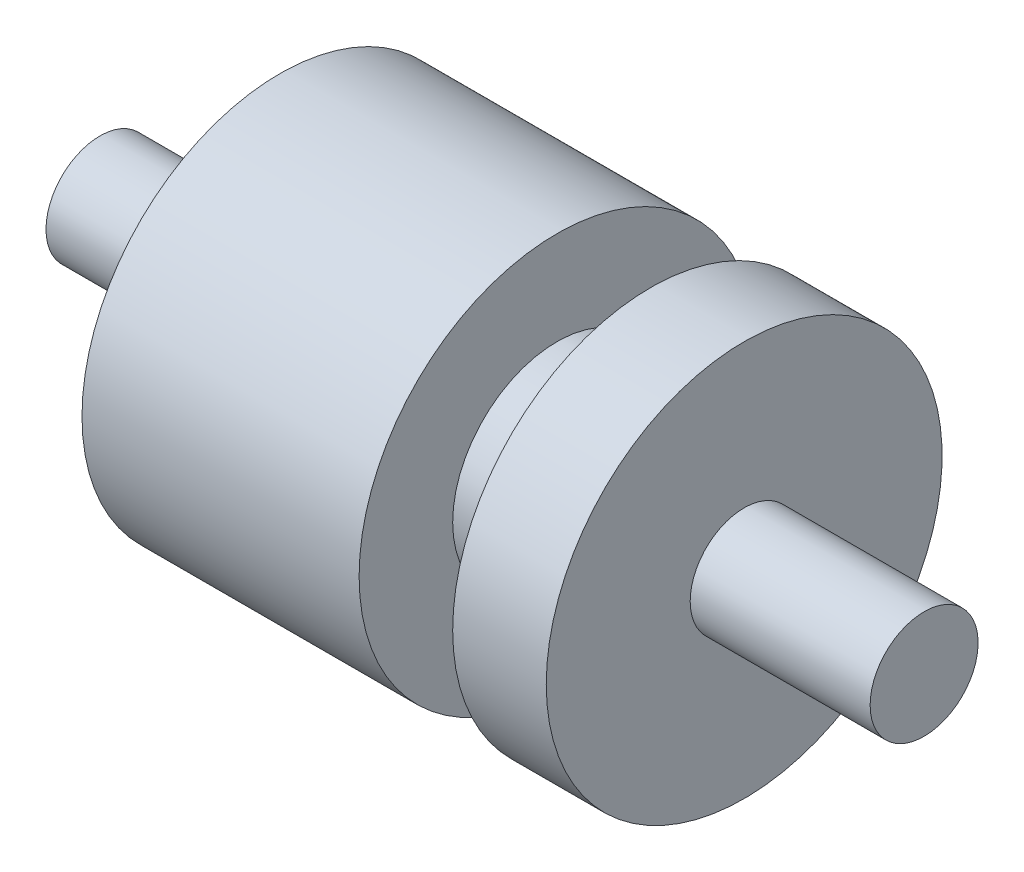
SolidWorks part; units mm, degrees
ref_plane "Alzado" through (0, 0, 0) normal (0, 0, 1) x (1, 0, 0)
ref_plane "Planta" through (0, 0, 0) normal (0, 1, 0) x (1, 0, 0)
ref_plane "Vista lateral" through (0, 0, 0) normal (1, 0, 0) x (0, 0, -1)
sketch "Croquis2" plane through (0, 0, 0) normal (0, 0, 1) x (1, 0, 0)
  line L0 (-68.0943, 0) -> (81.6733, 0) construction
  line L1 (-22.9, 1.5) -> (-17.9, 1.5)
  line L2 (-17.9, 1.5) -> (-17.9, 5.5)
  line L3 (-17.9, 5.5) -> (-10.2, 5.5)
  line L4 (-10.2, 5.5) -> (-10.2, 2.9)
  line L5 (-10.2, 2.9) -> (-7.6, 2.9)
  line L6 (-7.6, 2.9) -> (-7.6, 5.5)
  line L7 (-7.6, 5.5) -> (-5, 5.5)
  line L8 (-5, 5.5) -> (-5, 1.5)
  line L9 (-5, 1.5) -> (0, 1.5)
  line L10 (-22.9, 1.5) -> (-22.9, 0)
  line L11 (-22.9, 0) -> (0, 0)
  line L12 (0, 0) -> (0, 1.5)
  dimension "D1" = 5.5
  dimension "D2" = 1.5
  dimension "D3" = 1.5
  dimension "D4" = 5
  dimension "D5" = 5
  dimension "D6" = 2.9
  dimension "D7" = 5.5
  dimension "D8" = 7.7
  dimension "D9" = 2.6
  dimension "D10" = 2.6
revolve "Revolución1" add sketch "Croquis2" angle 360 about L0
